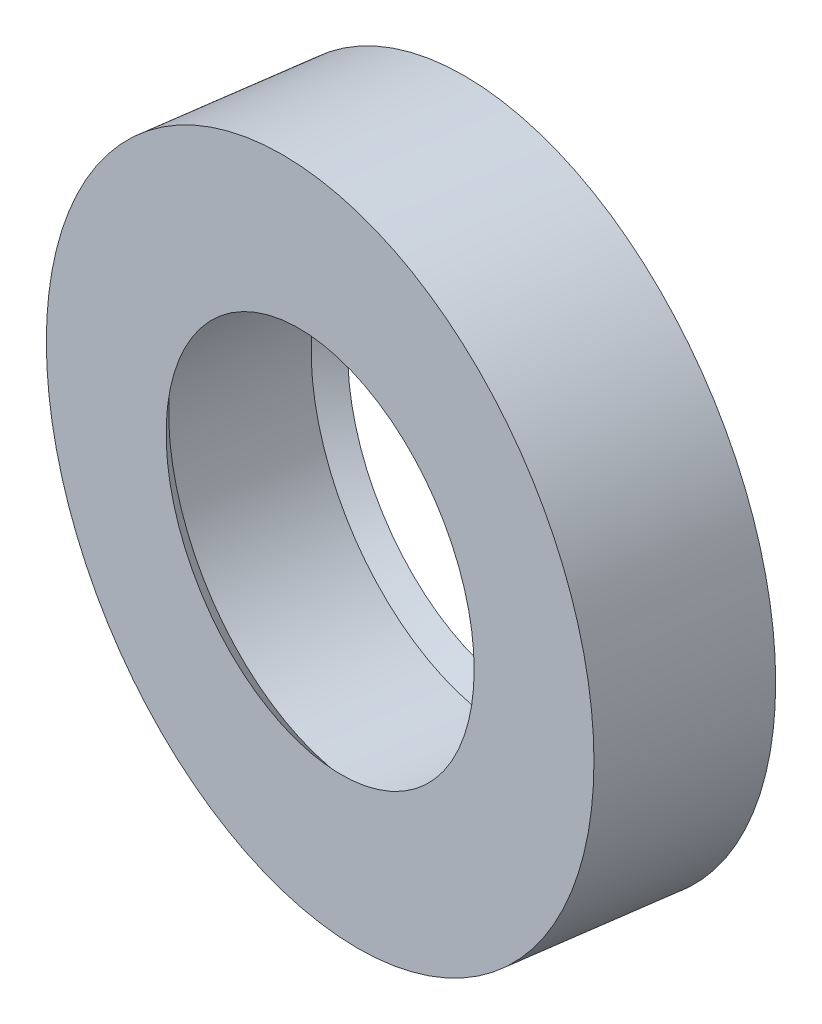
SolidWorks part; units mm, degrees
material "Rubber"
ref_plane "Front Plane" through (0, 0, 0) normal (0, 0, 1) x (1, 0, 0)
ref_plane "Top Plane" through (0, 0, 0) normal (0, 1, 0) x (1, 0, 0)
ref_plane "Right Plane" through (0, 0, 0) normal (1, 0, 0) x (0, 0, -1)
sketch "Sketch1" plane through (-20.1728, 5.2864, 55.6437) normal (0.9444, -0.3007, 0.1328) x (0.1393, 0, -0.9903)
  line L0 (44.5517, -18.2797) -> (45.2375, -19.0734) construction
  line L1 (45.2375, -19.0734) -> (50.2159, -19.0734) construction
  line L2 (50.9017, -18.2797) -> (50.9017, -19.0734) construction
  line L3 (50.2159, -19.0734) -> (50.9017, -18.2797) construction
  line L4 (50.9017, -23.8359) -> (50.9017, -19.0734) construction
  line L5 (44.5517, -23.8359) -> (50.9017, -23.8359) construction
  line L6 (44.5517, -23.8359) -> (44.5517, -19.0734) construction
  line L7 (44.5517, -19.0734) -> (44.5517, -18.2797) construction
  line L8 (44.5517, -18.2797) -> (45.2375, -19.0734)
  line L9 (45.2375, -19.0734) -> (50.2159, -19.0734)
  line L10 (50.9017, -18.2797) -> (50.9017, -19.0734)
  line L11 (50.2159, -19.0734) -> (50.9017, -18.2797)
  line L12 (50.9017, -23.8359) -> (50.9017, -19.0734)
  line L13 (44.5517, -23.8359) -> (50.9017, -23.8359)
  line L14 (44.5517, -23.8359) -> (44.5517, -19.0734)
  line L15 (44.5517, -19.0734) -> (44.5517, -18.2797)
  line L16 (22.0768, -11.1359) -> (73.3766, -11.1359) construction
  line L17 (22.0768, -11.1359) -> (73.3766, -11.1359)
revolve "Revolve1" add sketch "Sketch1" angle 360 about L17
